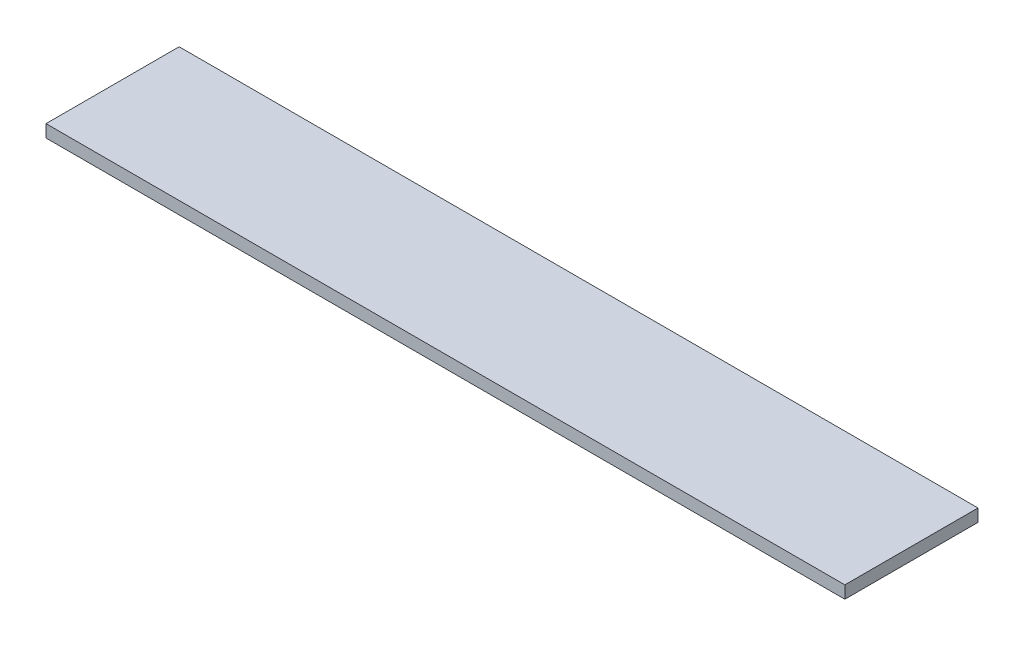
SolidWorks part; units mm, degrees
ref_plane "Front Plane" through (0, 0, 0) normal (0, 0, 1) x (1, 0, 0)
ref_plane "Top Plane" through (0, 0, 0) normal (0, 1, 0) x (1, 0, 0)
ref_plane "Right Plane" through (0, 0, 0) normal (1, 0, 0) x (0, 0, -1)
sketch "Sketch1" plane through (0, 0, 0) normal (0, 1, 0) x (1, 0, 0)
  line L1 (-609.6, 101.6) -> (609.6, 101.6)
  line L2 (-609.6, 101.6) -> (-609.6, -101.6)
  line L3 (-609.6, -101.6) -> (609.6, -101.6)
  line L4 (609.6, 101.6) -> (609.6, -101.6)
  line L5 (-609.6, 101.6) -> (609.6, -101.6) construction
  line L6 (-609.6, -101.6) -> (609.6, 101.6) construction
  point P0 (0, 0)
  dimension "D1" = 203.2
  dimension "D2" = 1219.2
extrude "Boss-Extrude1" add sketch "Sketch1" along normal blind 19.05
